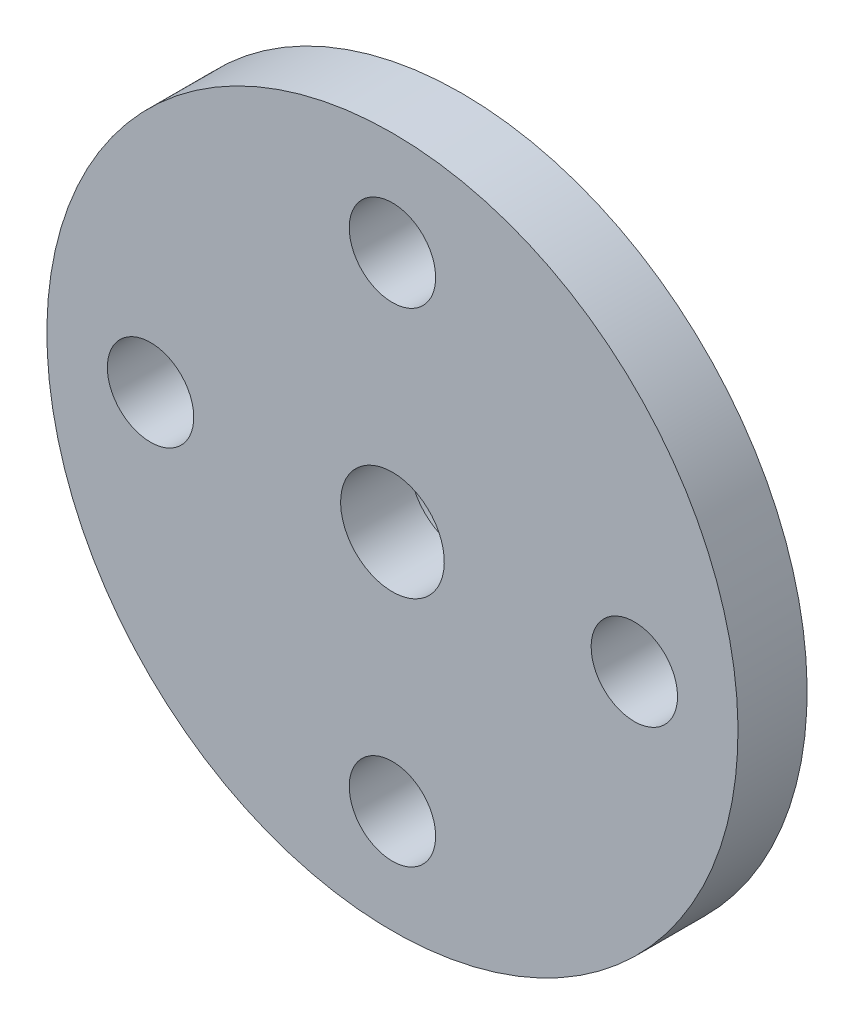
SolidWorks part; units mm, degrees
ref_plane "前视基准面" through (0, 0, 0) normal (0, 0, 1) x (1, 0, 0)
ref_plane "上视基准面" through (0, 0, 0) normal (0, 1, 0) x (1, 0, 0)
ref_plane "右视基准面" through (0, 0, 0) normal (1, 0, 0) x (0, 0, -1)
sketch "草图2" plane through (0, 0, 0) normal (1, 0, 0) x (0, 0, -1)
  line L0 (0, 0) -> (-50000, 0) construction
  line L1 (0, 0) -> (0, 50000) construction
  line L2 (-2, 1.5) -> (-2, 10)
  line L3 (-2, 10) -> (0, 10)
  line L4 (0, 10) -> (0, 5)
  line L5 (0, 5) -> (3.5, 5)
  line L6 (3.5, 5) -> (3.5, 3)
  line L7 (3.5, 3) -> (0, 3)
  line L8 (0, 3) -> (0, 1.5)
  line L9 (0, 1.5) -> (-2, 1.5)
  dimension "D1" = 1.5
  dimension "D2" = 5
  dimension "D3" = 3
  dimension "D4" = 2
  dimension "D5" = 10
  dimension "D6" = 2
  dimension "D7" = 3.5
revolve "旋转1" add sketch "草图2" angle 360 about L0
hole_wizard "M3 螺纹孔1" positions "3D草图1" profile "草图4" tap size "M3" standard "GB"
sketch3d "3D草图1"
  point P0 (0, 7, 2)
sketch "草图4" plane through (0, 7, 2) normal (1, 0, 0) x (0, -1, 0)
  line L0 (0, 0) -> (0, 8.2511)
  line L1 (0, 8.2511) -> (1.25, 7.5)
  line L2 (1.25, 7.5) -> (1.25, 0)
  line L5 (1.25, 0) -> (0, 0)
  line L10 (0, 8.2511) -> (-1.25, 7.5) construction
  line L11 (0, -6.35) -> (0, 107.95) construction
  dimension "螺纹孔钻头直径" = 2.5
  dimension "螺纹孔钻头深度" = 7.5
  dimension "导头角度" = 118
cosmetic thread "孔螺蚊线1" parameters "D1"=5.5, "D2"=3
pattern_circular "阵列(圆周)1" count 4 over 360 about axis through (0, 0, 0) along (0, 0, 1) of "M3 螺纹孔1"
